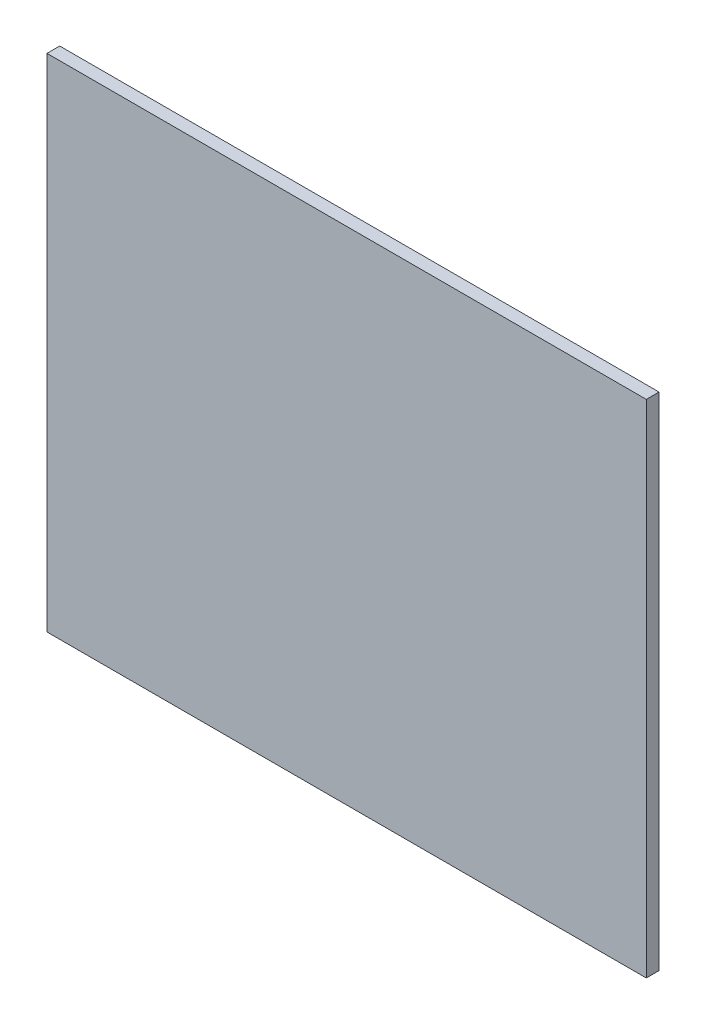
SolidWorks part; units mm, degrees
ref_plane "Ebene vorne" through (0, 0, 0) normal (0, 0, 1) x (1, 0, 0)
ref_plane "Ebene oben" through (0, 0, 0) normal (0, 1, 0) x (1, 0, 0)
ref_plane "Ebene rechts" through (0, 0, 0) normal (1, 0, 0) x (0, 0, -1)
sketch "Skizze1" plane through (0, 0, 0) normal (0, 0, 1) x (1, 0, 0)
  line L1 (0, 0) -> (23.5, 0)
  line L2 (0, 0) -> (0, 19.65)
  line L3 (0, 19.65) -> (23.5, 19.65)
  line L4 (23.5, 0) -> (23.5, 19.65)
  dimension "D1" = 23.5
  dimension "D2" = 19.65
extrude "Aufsatz-Linear austragen1" add sketch "Skizze1" along normal blind 0.5
